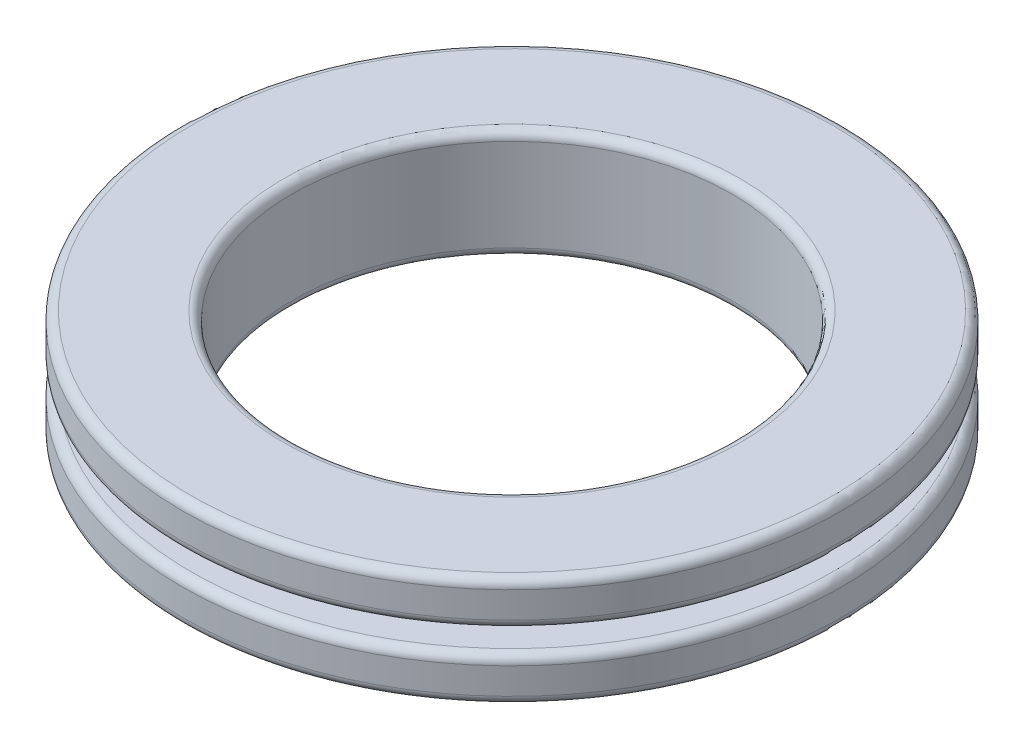
SolidWorks part; units mm, degrees
ref_plane "Front" through (0, 0, 0) normal (0, 0, 1) x (1, 0, 0)
ref_plane "Top" through (0, 0, 0) normal (0, 1, 0) x (1, 0, 0)
ref_plane "Right" through (0, 0, 0) normal (1, 0, 0) x (0, 0, -1)
sketch "Эскиз1" plane through (0, 0, 0) normal (0, 0, 1) x (1, 0, 0)
  line L0 (0, 0) -> (0, 68.434) construction
  line L1 (20, 0.8) -> (20, 9.2)
  line L2 (20.8, 0) -> (29.2, 0)
  line L3 (30, 0.8) -> (30, 3.2)
  line L4 (29.2, 4) -> (25.8, 4)
  line L5 (25, 4.8) -> (25, 5.2)
  line L6 (25.8, 6) -> (29.2, 6)
  line L7 (30, 6.8) -> (30, 9.2)
  line L8 (29.2, 10) -> (20.8, 10)
  arc A0 (20, 9.2) -> (20.8, 10) centre (20.8, 9.2) cw
  arc A1 (20, 0.8) -> (20.8, 0) centre (20.8, 0.8) ccw
  arc A2 (29.2, 0) -> (30, 0.8) centre (29.2, 0.8) ccw
  arc A3 (30, 3.2) -> (29.2, 4) centre (29.2, 3.2) ccw
  arc A4 (25.8, 4) -> (25, 4.8) centre (25.8, 4.8) cw
  arc A5 (25, 5.2) -> (25.8, 6) centre (25.8, 5.2) cw
  arc A6 (29.2, 6) -> (30, 6.8) centre (29.2, 6.8) ccw
  arc A7 (30, 9.2) -> (29.2, 10) centre (29.2, 9.2) ccw
  point P13 (20, 10)
  point P16 (20, 0)
  point P19 (30, 0)
  point P22 (30, 4)
  point P25 (25, 4)
  point P28 (25, 6)
  point P33 (30, 10)
  dimension "D8" = 0.8
  dimension "D1" = 10
  dimension "D2" = 20
  dimension "D3" = 30
  dimension "D4" = 4
  dimension "D5" = 2
  dimension "D6" = 25
  dimension "D7" = 10
revolve "Повернуть1" add sketch "Эскиз1" angle 360 about L0
